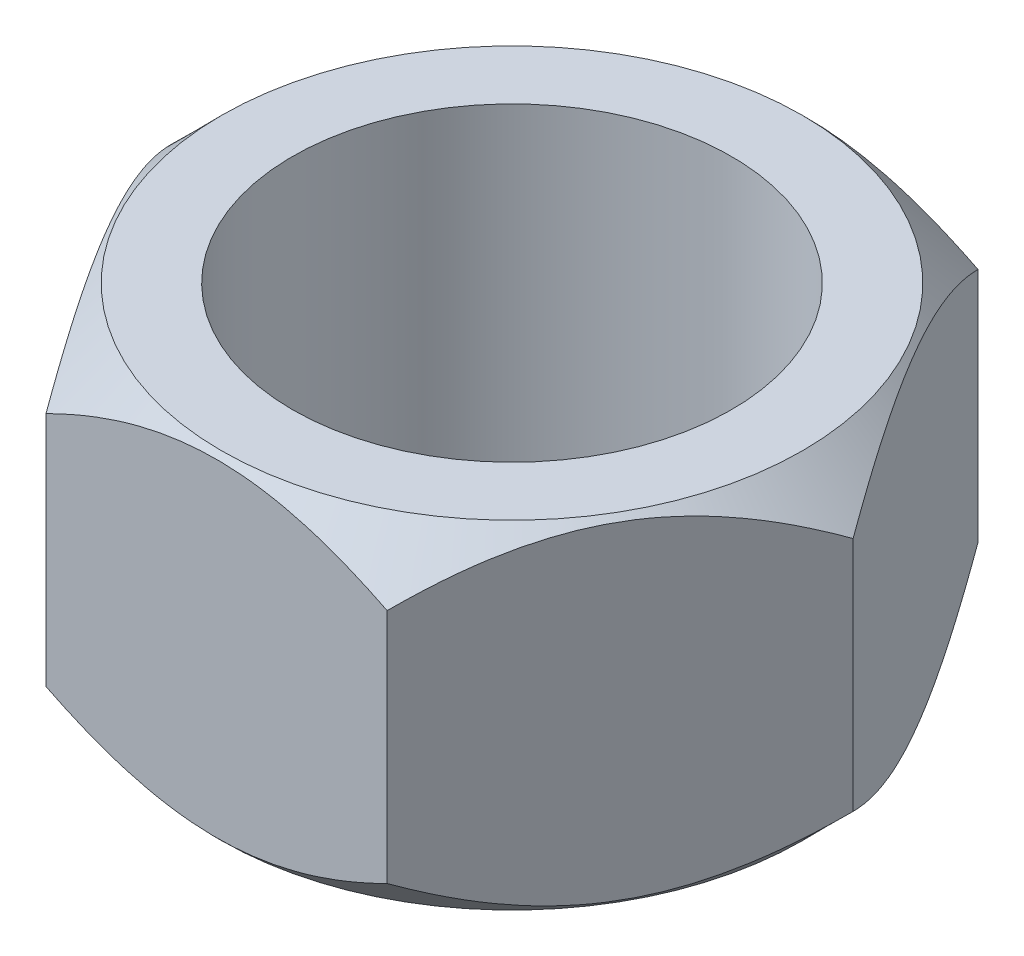
SolidWorks part; units mm, degrees
ref_plane "Front Plane" through (0, 0, 0) normal (0, 0, 1) x (1, 0, 0)
ref_plane "Top Plane" through (0, 0, 0) normal (0, 1, 0) x (1, 0, 0)
ref_plane "Right Plane" through (0, 0, 0) normal (1, 0, 0) x (0, 0, -1)
sketch "Sketch1" plane through (0, 0, 0) normal (0, 1, 0) x (1, 0, 0)
  line L0 (-0.2021, 0) -> (0.2021, 0) construction
  line L1 (0.101, 0.175) -> (-0.101, 0.175)
  line L2 (-0.101, 0.175) -> (-0.2021, 0)
  line L3 (-0.2021, 0) -> (-0.101, -0.175)
  line L4 (-0.101, -0.175) -> (0.101, -0.175)
  line L5 (0.101, -0.175) -> (0.2021, 0)
  line L6 (0.2021, 0) -> (0.101, 0.175)
  circle A0 centre (0, 0) radius 0.175 construction
  circle A1 centre (0, 0) radius 0.13
  dimension "D2" = 0.26
  dimension "D1" = 0.35
extrude "Boss-Extrude1" add sketch "Sketch1" along normal blind 0.2
sketch "Sketch3" plane through (0, 0, 0) normal (0, 0, 1) x (1, 0, 0)
  line L0 (0.1721, 0.2) -> (0.2021, 0.2)
  line L1 (0.101, 0.2) -> (0.2021, 0.2) construction
  line L2 (0.2021, 0.2) -> (0.2021, 0.17)
  line L3 (0.2021, 0.2) -> (0.2021, 0) construction
  line L4 (0.2021, 0.17) -> (0.1721, 0.2)
  line L5 (-0.2021, 0.1) -> (0.2021, 0.1) construction
  line L6 (-0.2021, 0.2) -> (-0.2021, 0) construction
  line L7 (0.2021, 0) -> (0.2021, 0.03)
  line L8 (0.1721, 0) -> (0.2021, 0)
  line L9 (0.2021, 0.03) -> (0.1721, 0)
  line L10 (0, 0.2) -> (0, 0) construction
  line L11 (-0.101, 0.2) -> (0.101, 0.2) construction
  dimension "D1" = 0.03
revolve "Cut-Revolve5" cut sketch "Sketch3" angle 360 about L10
